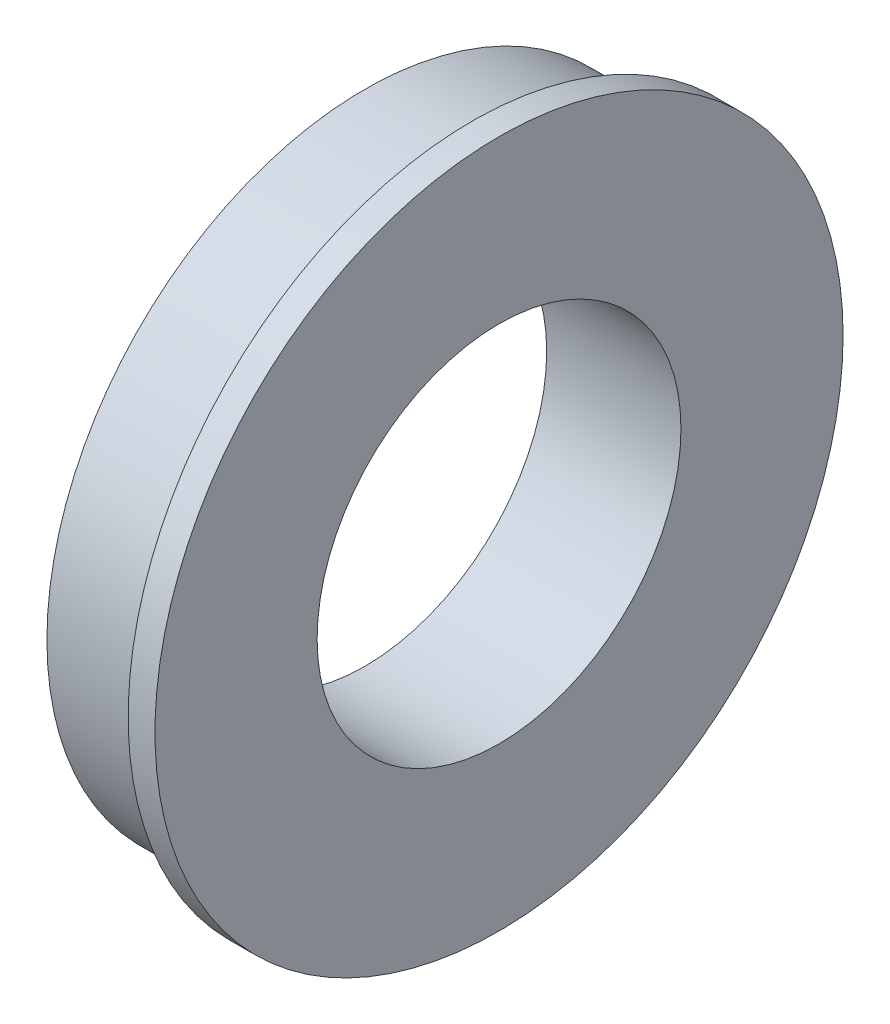
SolidWorks part; units mm, degrees
ref_plane "Ebene vorne" through (0, 0, 0) normal (0, 0, 1) x (1, 0, 0)
ref_plane "Ebene oben" through (0, 0, 0) normal (0, 1, 0) x (1, 0, 0)
ref_plane "Ebene rechts" through (0, 0, 0) normal (1, 0, 0) x (0, 0, -1)
sketch "Sketch1" plane through (0, 0, 0) normal (1, 0, 0) x (0, 0, -1)
  circle A0 centre (0, 0) radius 27.1
  circle A1 centre (0, 0) radius 47.35
  dimension "D1" = 54.2
  dimension "D2" = 94.7
extrude "Boss-Extrude1" add sketch "Sketch1" along normal blind 16
sketch "Sketch2" plane through (16, 0, 0) normal (1, 0, 0) x (0, 0, -1)
  circle A0 centre (0, 0) radius 51.25
  circle A1 centre (0, 0) radius 27.1
  dimension "D1" = 102.5
extrude "Boss-Extrude2" add sketch "Sketch2" along normal blind 4
